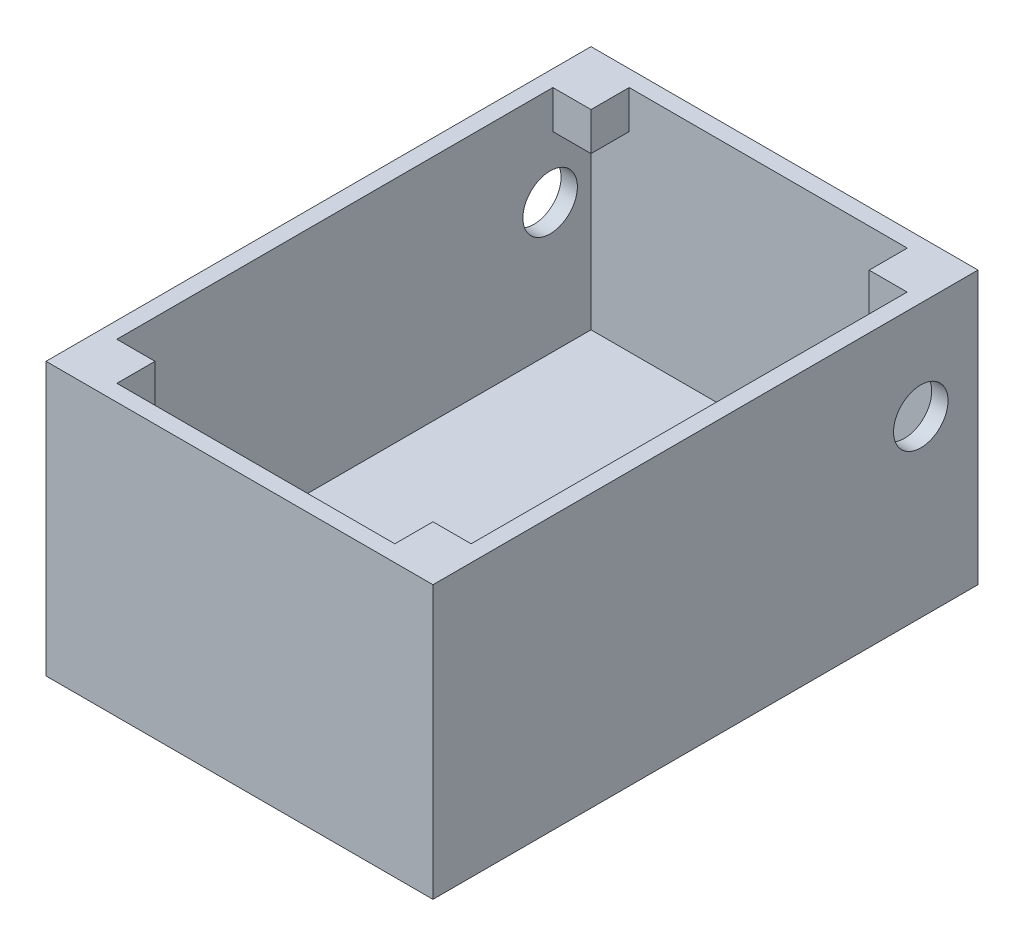
SolidWorks part; units mm, degrees
ref_plane "Front Plane" through (0, 0, 0) normal (0, 0, 1) x (1, 0, 0)
ref_plane "Top Plane" through (0, 0, 0) normal (0, 1, 0) x (1, 0, 0)
ref_plane "Right Plane" through (0, 0, 0) normal (1, 0, 0) x (0, 0, -1)
sketch "Sketch1" plane through (0, 0, 0) normal (0, 1, 0) x (1, 0, 0)
  line L0 (-61.6962, 29.5) -> (-61.6962, -70.5) construction
  line L1 (-61.6962, 26.5) -> (-64.6962, 26.5) construction
  line L2 (-61.6962, -32.5) -> (-10.6962, -32.5) construction
  line L7 (-61.6962, 26.5) -> (-61.6962, -32.5) construction
  line L8 (-10.6962, -32.5) -> (-10.6962, 26.5) construction
  line L9 (-10.6962, 26.5) -> (-61.6962, 26.5) construction
  line L10 (-10.6962, -32.5) -> (-10.6962, -35.5) construction
  line L12 (-61.6962, 26.5) -> (-61.6962, 29.5) construction
  line L13 (-61.6962, 29.5) -> (-27.6962, 29.5) construction
  line L14 (-27.6962, 29.5) -> (6.3038, 29.5) construction
  line L15 (-64.6962, 29.5) -> (6.3038, 29.5)
  line L16 (-64.6962, 29.5) -> (-64.6962, -70.5)
  line L17 (-64.6962, -70.5) -> (6.3038, -70.5)
  line L18 (6.3038, 29.5) -> (6.3038, -70.5)
  point P5 (0, 0)
extrude "Boss-Extrude1" add sketch "Sketch1" along normal blind 50 contours L18 L17 L16 L15
sketch "Sketch2" plane through (0, 50, 0) normal (0, 1, 0) x (1, 0, 0)
  line L4 (-61.6962, 29.5) -> (-61.6962, 26.5) construction
  line L5 (-64.6962, 29.5) -> (6.3038, 29.5) construction
  line L7 (6.3038, -67.5) -> (3.3038, -67.5) construction
  line L8 (6.3038, 29.5) -> (6.3038, -70.5) construction
  line L9 (-61.6962, 26.5) -> (3.3038, 26.5)
  line L10 (-61.6962, 26.5) -> (-61.6962, -67.5)
  line L11 (-61.6962, -67.5) -> (3.3038, -67.5)
  line L12 (3.3038, 26.5) -> (3.3038, -67.5)
extrude "Cut-Extrude1" cut sketch "Sketch2" against normal blind 47
sketch "Sketch3" plane through (0, 3, 0) normal (0, 1, 0) x (1, 0, 0)
  line L0 (-61.6962, 26.5) -> (-61.6962, 23.8379) construction
  line L1 (-61.6962, 26.5) -> (-61.6962, -67.5) construction
  line L2 (-61.6962, 23.8379) -> (-61.6962, -35.1621) construction
  line L3 (-61.6962, 26.5) -> (-61.6962, -67.5) construction
  line L4 (-61.6962, -35.1621) -> (-10.6962, -35.1621) construction
  line L6 (-61.6962, 26.5) -> (-10.6962, 26.5)
  line L7 (-61.6962, 26.5) -> (-61.6962, -35.1621)
  line L8 (-61.6962, -35.1621) -> (-10.6962, -35.1621)
  line L9 (-10.6962, 26.5) -> (-10.6962, -35.1621)
extrude "Boss-Extrude2" add sketch "Sketch3" along normal blind 5
sketch "Sketch4" plane through (-61.6962, 0, 0) normal (1, 0, 0) x (0, 0, -1)
  line L2 (19, 8) -> (19, 32) construction
  line L3 (26.5, 8) -> (-35.1621, 8) construction
  circle A0 centre (19, 32) radius 5
extrude "Cut-Extrude2" cut sketch "Sketch4" against normal through all both and the other way through all contours A0
sketch "Sketch5" plane through (0, 50, 0) normal (0, 1, 0) x (1, 0, 0)
  line L1 (-64.6962, 29.5) -> (-54.6962, 29.5)
  line L2 (-64.6962, 29.5) -> (-64.6962, 19.5)
  line L3 (-64.6962, 19.5) -> (-54.6962, 19.5)
  line L4 (-54.6962, 29.5) -> (-54.6962, 19.5)
  line L5 (6.3038, 29.5) -> (-3.6674, 29.5)
  line L6 (6.3038, 29.5) -> (6.3038, 19.5)
  line L7 (6.3038, 19.5) -> (-3.6674, 19.5)
  line L8 (-3.6674, 29.5) -> (-3.6674, 19.5)
  line L9 (6.3038, -70.5) -> (-3.6962, -70.5)
  line L10 (6.3038, -70.5) -> (6.3038, -60.5)
  line L11 (6.3038, -60.5) -> (-3.6962, -60.5)
  line L12 (-3.6962, -70.5) -> (-3.6962, -60.5)
  line L13 (-64.6962, -70.5) -> (-54.6962, -70.5)
  line L14 (-64.6962, -70.5) -> (-64.6962, -60.5)
  line L15 (-64.6962, -60.5) -> (-54.6962, -60.5)
  line L16 (-54.6962, -70.5) -> (-54.6962, -60.5)
extrude "Boss-Extrude3" add sketch "Sketch5" against normal blind 7
